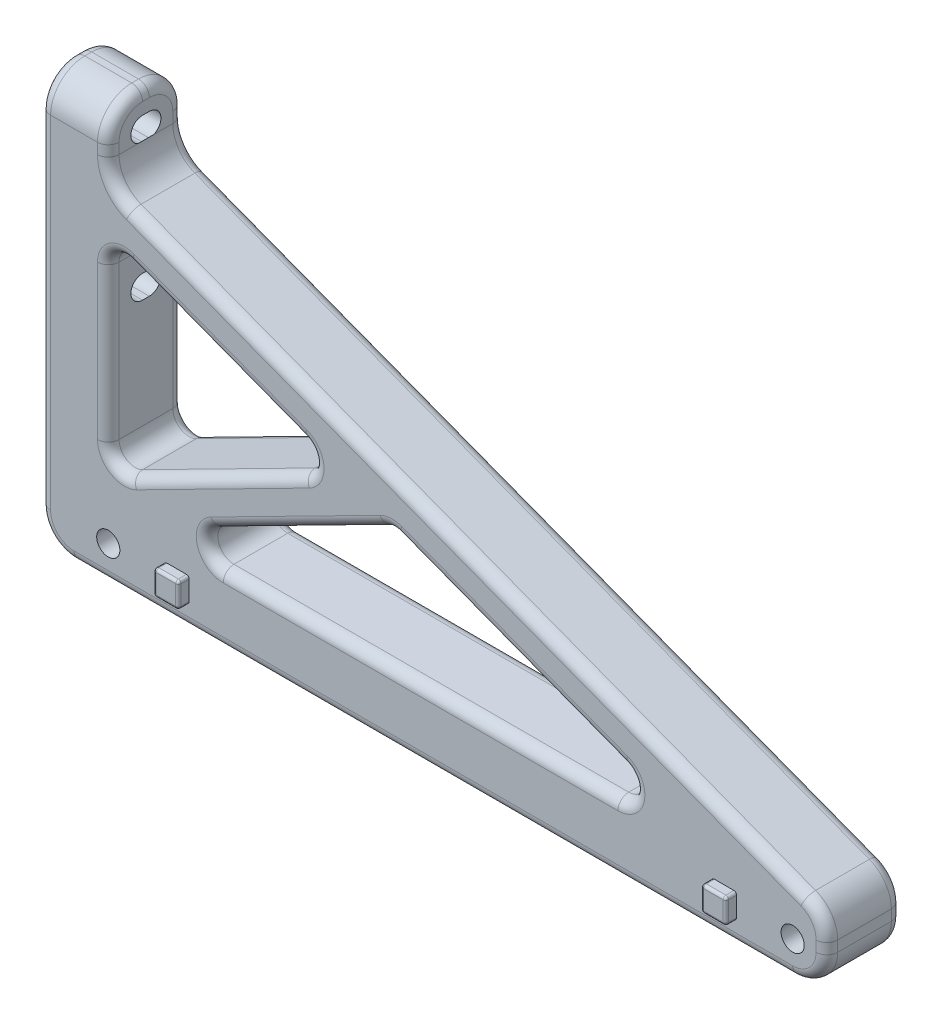
SolidWorks part; units mm, degrees
ref_plane "Front Plane" through (0, 0, 0) normal (0, 0, 1) x (1, 0, 0)
ref_plane "Top Plane" through (0, 0, 0) normal (0, 1, 0) x (1, 0, 0)
ref_plane "Right Plane" through (0, 0, 0) normal (1, 0, 0) x (0, 0, -1)
sketch "Sketch1" plane through (0, 0, 0) normal (0, 0, 1) x (1, 0, 0)
  line L0 (-12.7, 57.15) -> (-12.7, -6.35)
  line L1 (-12.7, -6.35) -> (133.35, -6.35)
  line L2 (133.35, -6.35) -> (133.35, 6.35)
  line L3 (133.35, 6.35) -> (0, 57.15)
  line L4 (0, 57.15) -> (-12.7, 57.15)
  line L5 (0, 48.5892) -> (0, 6.35)
  line L6 (0, 6.35) -> (110.8778, 6.35)
  line L7 (110.8778, 6.35) -> (0, 48.5892)
  line L8 (0, 6.35) -> (47.472, 30.5046) construction
  line L9 (8.8205, 6.35) -> (52.516, 28.5831)
  line L10 (0, 10.838) -> (42.428, 32.4261)
  line L12 (-12.7, 57.15) -> (0, 57.15)
  line L13 (-12.7, 57.15) -> (-12.7, 69.85)
  line L14 (-12.7, 69.85) -> (0, 69.85)
  line L15 (0, 57.15) -> (0, 69.85)
  circle A0 centre (0, 0) radius 2.15
  circle A1 centre (127, 0) radius 2.15
  dimension "D1" = 4.3
  dimension "D2" = 127
  dimension "D3" = 6.35
  dimension "D4" = 12.7
  dimension "D5" = 6.35
  dimension "D6" = 12.7
  dimension "D7" = 63.5
  dimension "D8" = 12.7
  dimension "D9" = 12.7
  dimension "D10" = 8
  dimension "D11" = 8
  dimension "D12" = 12.7
  dimension "D13" = 50.8
extrude "Boss-Extrude1" add sketch "Sketch1" along normal blind 13.97
fillet "Fillet1" radius 3 6 edges at (110.8778, 6.35, 6.985) (52.516, 28.5831, 6.985) (8.8205, 6.35, 6.985) (0, 10.838, 6.985) (42.428, 32.4261, 6.985) (0, 48.5892, 6.985)
fillet "Fillet2" radius 6.35 6 edges at (133.35, 6.35, 6.985) (133.35, -6.35, 6.985) (-12.7, -6.35, 6.985) (0, 57.15, 6.985) (-6.35, 69.85, 0) (-6.35, 69.85, 13.97)
sketch "Sketch2" plane through (0, 0, 0) normal (1, 0, 0) x (0, 0, -1)
  line L1 (-7.62, 63.5) -> (-6.35, 63.5) construction
  line L2 (-7.62, 65.65) -> (-6.35, 65.65)
  line L3 (-7.62, 61.35) -> (-6.35, 61.35)
  line L4 (0, 61.5261) -> (0, 63.5) construction
  line L5 (-13.97, 61.5261) -> (-13.97, 55.5921) construction
  line L6 (-7.62, 69.85) -> (-6.35, 69.85) construction
  line L7 (-7.62, 35.95) -> (-6.35, 35.95)
  line L8 (-7.62, 40.25) -> (-6.35, 40.25)
  line L9 (-7.62, 38.1) -> (-6.35, 38.1) construction
  arc A1 (-7.62, 65.65) -> (-7.62, 61.35) centre (-7.62, 63.5) ccw
  arc A2 (-6.35, 61.35) -> (-6.35, 65.65) centre (-6.35, 63.5) ccw
  arc A3 (-7.62, 40.25) -> (-7.62, 35.95) centre (-7.62, 38.1) ccw
  arc A4 (-6.35, 35.95) -> (-6.35, 40.25) centre (-6.35, 38.1) ccw
  point P2 (-6.985, 63.5)
  point P16 (-6.985, 38.1)
  dimension "D1" = 2.15
  dimension "D2" = 6.35
  dimension "D3" = 6.35
  dimension "D4" = 6.35
  dimension "D6" = 25.4
  dimension "D5" = 2
extrude "Cut-Extrude1" cut sketch "Sketch2" against normal through all
fillet "Fillet3" radius 2 48 edges at (1.4318, 13.173, 13.97) (1.4318, 13.173, 0) (0, 29.9832, 13.97) (0, 29.9832, 0) (1.2976, 46.7062, 13.97) (1.2976, 46.7062, 0) (20.0864, 40.9372, 13.97) (20.0864, 40.9372, 0) (38.0326, 32.1914, 13.97) (38.0326, 32.1914, 0) (97.5262, 8.807, 13.97) (97.5262, 8.807, 0) (57.9538, 6.35, 13.97) (57.9538, 6.35, 0) (18.4146, 8.6505, 13.97) (18.4146, 8.6505, 0) (35.651, 20.0018, 0) (35.651, 20.0018, 13.97) (52.531, 28.3018, 13.97) (52.531, 28.3018, 0) (74.7013, 20.1315, 0) (74.7013, 20.1315, 13.97) (20.3789, 21.2072, 0) (20.3789, 21.2072, 13.97) (132.2286, 5.5772, 13.97) (132.2286, 5.5772, 0) (133.35, 0.9869, 13.97) (133.35, 0.9869, 0) (131.4901, -4.4901, 13.97) (131.4901, -4.4901, 0) (60.325, -6.35, 0) (60.325, -6.35, 13.97) (-10.8401, -4.4901, 13.97) (-10.8401, -4.4901, 0) (-12.7, 31.75, 13.97) (-12.7, 67.9901, 12.1101) (-12.7, 69.85, 6.985) (-12.7, 67.9901, 1.8599) (-12.7, 31.75, 0) (66.675, 31.75, 0) (66.675, 31.75, 13.97) (1.1214, 57.9228, 13.97) (1.1214, 57.9228, 0) (0, 62.5131, 0) (0, 67.9901, 1.8599) (0, 69.85, 6.985) (0, 67.9901, 12.1101) (0, 62.5131, 13.97)
sketch "Sketch3" plane through (0, 0, 13.97) normal (0, 0, 1) x (1, 0, 0)
  line L1 (0, 0) -> (127, 0) construction
  line L3 (10.3886, 2.3114) -> (15.0114, 2.3114)
  line L4 (10.3886, 2.3114) -> (10.3886, -2.3114)
  line L5 (10.3886, -2.3114) -> (15.0114, -2.3114)
  line L6 (15.0114, 2.3114) -> (15.0114, -2.3114)
  line L7 (10.3886, 2.3114) -> (15.0114, -2.3114) construction
  line L8 (10.3886, -2.3114) -> (15.0114, 2.3114) construction
  line L9 (111.9886, 2.3114) -> (116.6114, 2.3114)
  line L10 (111.9886, 2.3114) -> (111.9886, -2.3114)
  line L11 (111.9886, -2.3114) -> (116.6114, -2.3114)
  line L12 (116.6114, 2.3114) -> (116.6114, -2.3114)
  line L13 (111.9886, 2.3114) -> (116.6114, -2.3114) construction
  line L14 (111.9886, -2.3114) -> (116.6114, 2.3114) construction
  point P0 (12.7, 0)
  point P9 (114.3, 0)
  point P14 (116.6114, 0)
  dimension "D1" = 4.6228
  dimension "D2" = 12.7
  dimension "D3" = 4.6228
  dimension "D4" = 12.7
extrude "Boss-Extrude2" add sketch "Sketch3" along normal blind 2
fillet "Fillet4" radius 0.508 16 edges at (114.3, -2.3114, 15.97) (111.9886, 0, 15.97) (114.3, 2.3114, 15.97) (116.6114, 0, 15.97) (12.7, -2.3114, 15.97) (10.3886, 0, 15.97) (12.7, 2.3114, 15.97) (15.0114, 0, 15.97) (116.6114, 2.3114, 14.97) (116.6114, -2.3114, 14.97) (111.9886, -2.3114, 14.97) (111.9886, 2.3114, 14.97) (10.3886, -2.3114, 14.97) (15.0114, -2.3114, 14.97) (10.3886, 2.3114, 14.97) (15.0114, 2.3114, 14.97)
